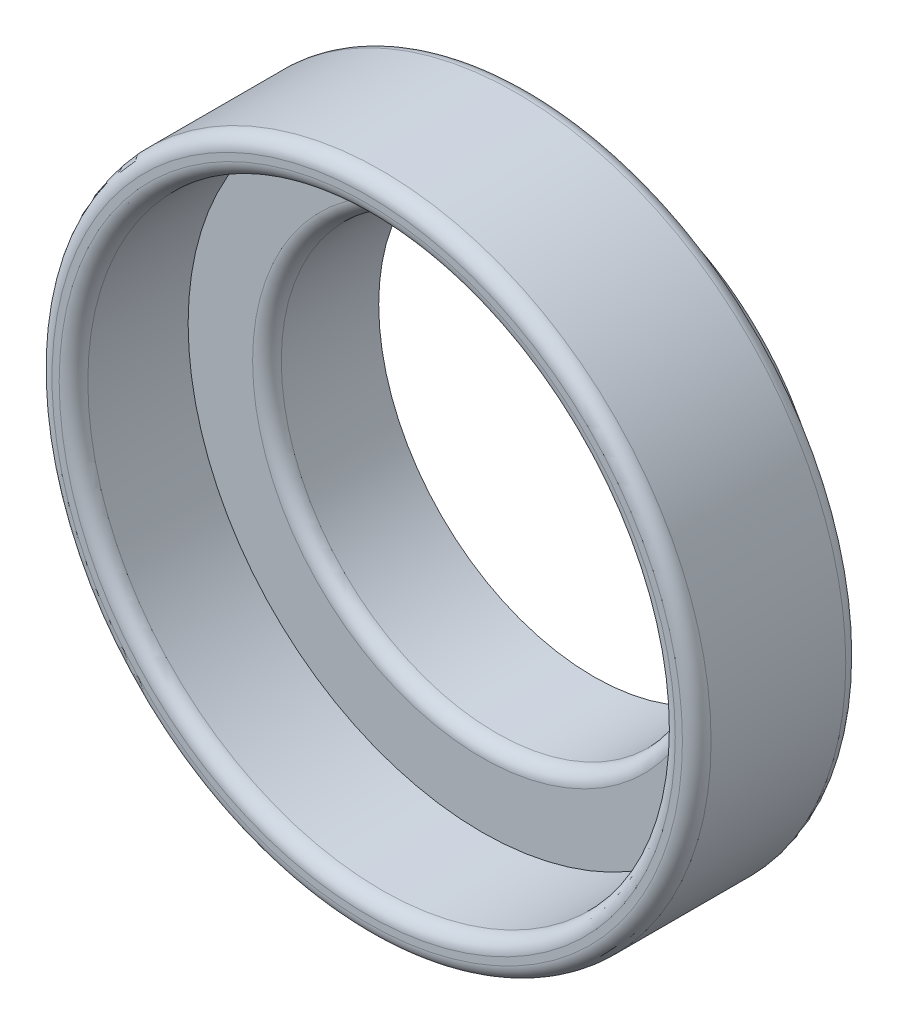
SolidWorks part; units mm, degrees
ref_plane "Front Plane" through (0, 0, 0) normal (0, 0, 1) x (1, 0, 0)
ref_plane "Top Plane" through (0, 0, 0) normal (0, 1, 0) x (1, 0, 0)
ref_plane "Right Plane" through (0, 0, 0) normal (1, 0, 0) x (0, 0, -1)
sketch "Sketch1" plane through (0, 0, 0) normal (0, 0, 1) x (1, 0, 0)
  circle A0 centre (0, 0) radius 23
  dimension "D1" = 46
extrude "Boss-Extrude1" add sketch "Sketch1" along normal blind 11.4
sketch "Sketch2" plane through (0, 0, 11.4) normal (0, 0, 1) x (1, 0, 0)
  circle A0 centre (0, 0) radius 20.5
  dimension "D1" = 41
extrude "Cut-Extrude1" cut sketch "Sketch2" against normal blind 8
sketch "Sketch3" plane through (0, 0, 3.4) normal (0, 0, 1) x (1, 0, 0)
  circle A0 centre (0, 0) radius 16.99
  dimension "D1" = 33.98
extrude "Boss-Extrude2" add sketch "Sketch3" against normal blind 7.8
sketch "Sketch4" plane through (0, 0, 3.4) normal (0, 0, 1) x (1, 0, 0)
  circle A0 centre (0, 0) radius 15
  dimension "34" = 30
extrude "Cut-Extrude2" cut sketch "Sketch4" against normal through all
fillet "Fillet1" radius 1 1 edges at (15, 0, 3.4)
fillet "Fillet3" radius 1 3 edges at (20.5, 0, 11.4) (23, 0, 11.4) (16.99, 0, -4.4)
fillet "Fillet4" radius 1 1 edges at (23, 0, 0)
